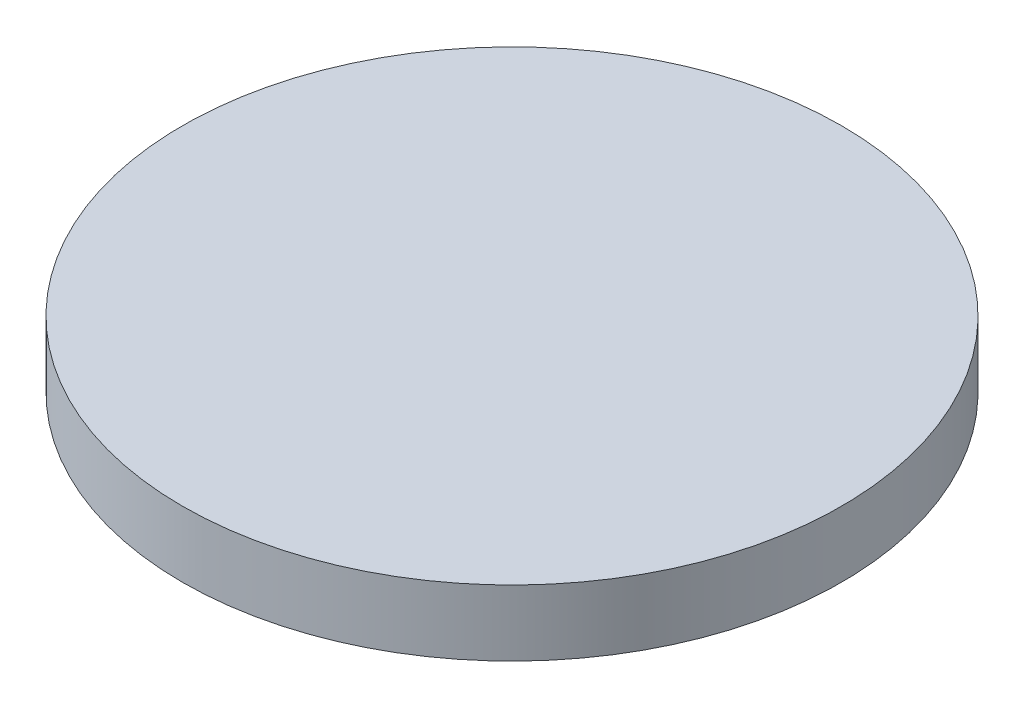
SolidWorks part; units mm, degrees
ref_plane "Front Plane" through (0, 0, 0) normal (0, 0, 1) x (1, 0, 0)
ref_plane "Top Plane" through (0, 0, 0) normal (0, 1, 0) x (1, 0, 0)
ref_plane "Right Plane" through (0, 0, 0) normal (1, 0, 0) x (0, 0, -1)
sketch "Sketch1" plane through (0, 0, 0) normal (0, 1, 0) x (1, 0, 0)
  circle A0 centre (0, 0) radius 20
  dimension "D1" = 40
extrude "Boss-Extrude1" add sketch "Sketch1" along normal blind 4
ref_plane "Plane1" through (0, 0, 0) normal (0, -1, 0) x (-1, 0, 0)
sketch "Sketch2" plane through (0, 0, 0) normal (0, -1, 0) x (-1, 0, 0)
  circle A0 centre (0, 0) radius 1
  dimension "D1" = 2
extrude "Cut-Extrude1" cut sketch "Sketch2" against normal blind 0.5
